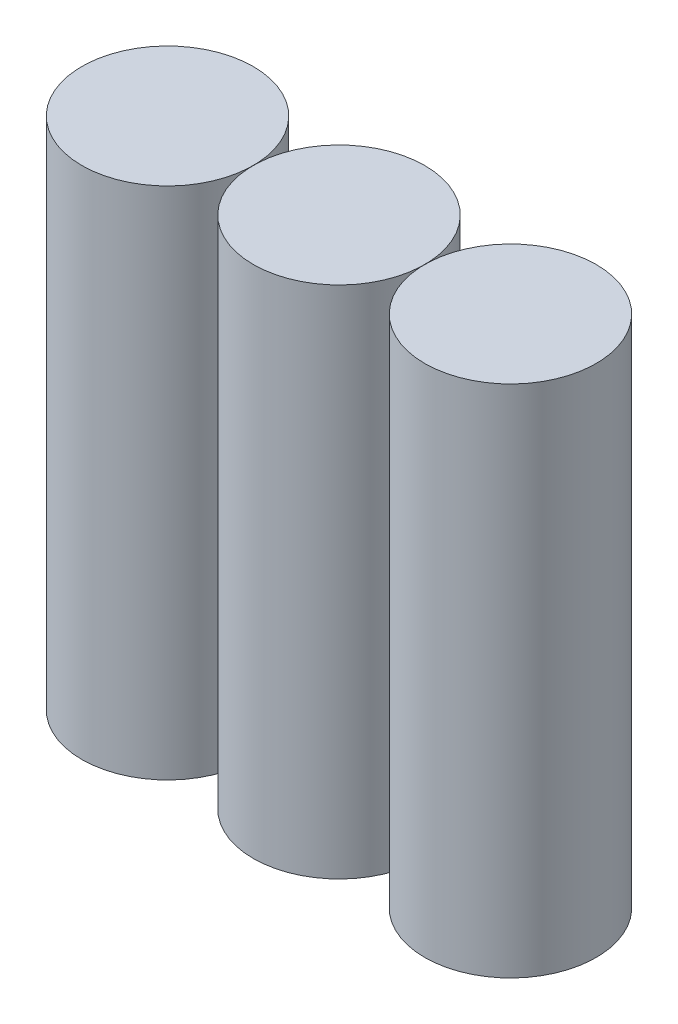
SolidWorks part; units mm, degrees
ref_plane "Front Plane" through (0, 0, 0) normal (0, 0, 1) x (1, 0, 0)
ref_plane "Top Plane" through (0, 0, 0) normal (0, 1, 0) x (1, 0, 0)
ref_plane "Right Plane" through (0, 0, 0) normal (1, 0, 0) x (0, 0, -1)
sketch "Sketch1" plane through (0, 0, 0) normal (0, 1, 0) x (1, 0, 0)
  line L0 (0, 0) -> (25.248, 0) construction
  circle A0 centre (0, 0) radius 2.5
  circle A2 centre (5, 0) radius 2.5
  circle A3 centre (-5, 0) radius 2.5
  point P8 (2.5, 0)
  point P10 (2.5, 0)
  point P11 (-2.5, 0)
  point P12 (-2.5, 0)
  point P13 (-7.5, 0)
  point P14 (7.5, 0)
  dimension "D1" = 5
  dimension "D2" = 5
  dimension "D3" = 5
extrude "Boss-Extrude1" add sketch "Sketch1" along normal blind 15 contours L0 A3 | A3 L0 | L0 A0 | A0 L0 | L0 A2 | A2 L0
